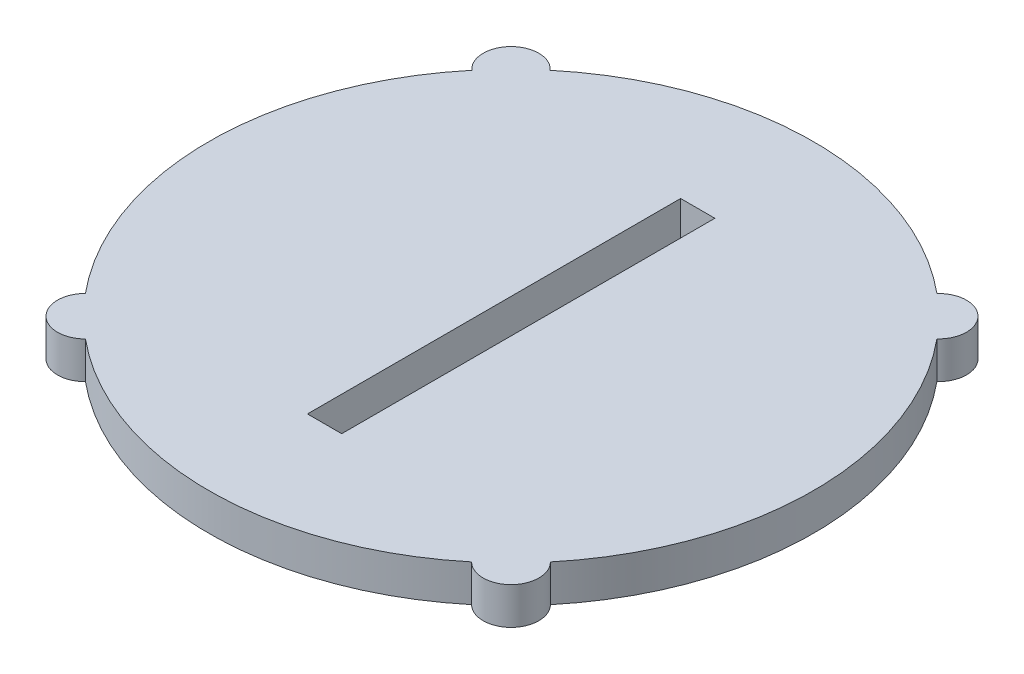
SolidWorks part; units mm, degrees
ref_plane "Front Plane" through (0, 0, 0) normal (0, 0, 1) x (1, 0, 0)
ref_plane "Top Plane" through (0, 0, 0) normal (0, 1, 0) x (1, 0, 0)
ref_plane "Right Plane" through (0, 0, 0) normal (1, 0, 0) x (0, 0, -1)
sketch "Sketch1" plane through (0, 0, 0) normal (0, 1, 0) x (1, 0, 0)
  line L0 (-48.6027, 20.883) -> (-44.9027, 20.883)
  line L1 (-48.6027, 41.033) -> (-44.9027, 41.033)
  line L2 (-48.6027, 41.033) -> (-48.6027, 0.733)
  line L3 (-48.6027, 0.733) -> (-44.9027, 0.733)
  line L4 (-44.9027, 41.033) -> (-44.9027, 0.733)
  line L5 (-46.7527, 20.883) -> (-46.7527, 26.6908) construction
  arc A0 (-71.8777, 41.7339) -> (-71.8628, 0.0142) centre (-46.7527, 20.883) ccw
  arc A1 (-21.6366, 41.7445) -> (-25.8732, 45.9842) centre (-23.6574, 43.9618) ccw
  arc A2 (-71.8628, 0.0142) -> (-67.6036, -4.242) centre (-69.7332, -2.1139) ccw
  arc A3 (-71.8777, 41.7339) -> (-71.8689, 41.7445) centre (-46.7527, 20.883) cw
  arc A4 (-71.8689, 41.7445) -> (-67.6322, 45.9842) centre (-69.8481, 43.9618) cw
  arc A5 (-67.6036, -4.242) -> (-25.9019, -4.242) centre (-46.7527, 20.883) ccw
  arc A6 (-21.6427, 0.0142) -> (-21.6366, 41.7445) centre (-46.7527, 20.883) ccw
  arc A7 (-25.8732, 45.9842) -> (-43.6914, 53.3892) centre (-46.7527, 20.883) ccw
  arc A8 (-21.6427, 0.0142) -> (-25.9019, -4.242) centre (-23.7723, -2.1139) cw
  arc A9 (-67.6322, 45.9842) -> (-43.6914, 53.3892) centre (-46.7527, 20.883) cw
  arc A10 (-21.6427, 0.0142) -> (-14.2359, 17.937) centre (-46.7527, 20.883) ccw
  point P9 (-34.2228, 23.2248)
  point P10 (-46.7527, 20.883)
  point P11 (-34.2228, 23.2248)
  point P15 (-46.7527, 20.883)
  point P26 (-34.2228, 23.233)
  dimension "D1" = 6
  dimension "D2" = 40.3
  dimension "D4" = 3.7
extrude "Boss-Extrude1" add sketch "Sketch1" along normal blind 4
